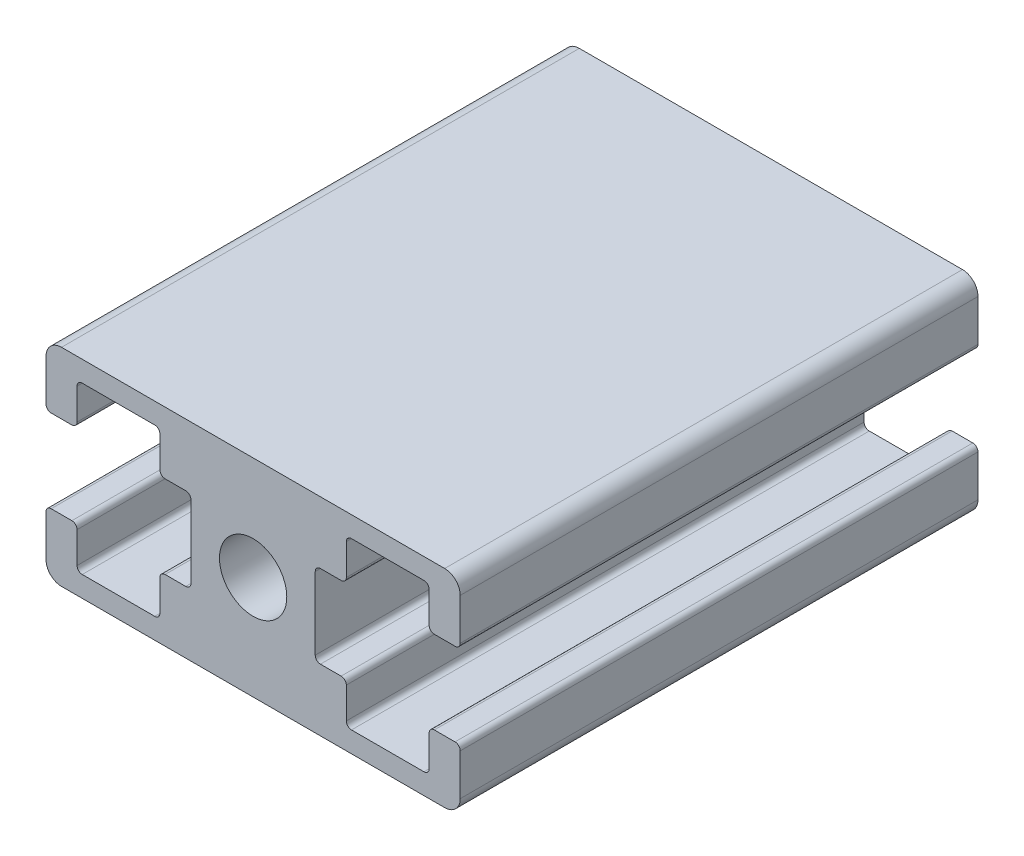
SolidWorks part; units mm, degrees
material "6063-T5"
ref_plane "Front Plane" through (0, 0, 0) normal (0, 0, 1) x (1, 0, 0)
ref_plane "Top Plane" through (0, 0, 0) normal (0, 1, 0) x (1, 0, 0)
ref_plane "Right Plane" through (0, 0, 0) normal (1, 0, 0) x (0, 0, -1)
sketch "Sketch1" plane through (0, 0, 0) normal (0, 0, 1) x (1, 0, 0)
  line L0 (1.5, 0) -> (38.5, 0)
  line L1 (40, 1.5) -> (40, 5.5)
  line L2 (38.5, 20) -> (1.5, 20)
  line L3 (0, 18.5) -> (0, 14.5)
  line L4 (0.5, 14) -> (2.5, 14)
  line L5 (0.5, 6) -> (2.5, 6)
  line L6 (39.5, 14) -> (37.5, 14)
  line L7 (39.5, 6) -> (37.5, 6)
  line L8 (40, 14.5) -> (40, 18.5)
  line L9 (0, 5.5) -> (0, 1.5)
  line L10 (37, 14.5) -> (37, 17.5)
  line L11 (37, 5.5) -> (37, 2.5)
  line L12 (3, 14.5) -> (3, 17.5)
  line L13 (3, 5.5) -> (3, 2.5)
  line L14 (3.5, 18) -> (10.5, 18)
  line L15 (11, 17.5) -> (11, 14.5)
  line L16 (26, 13.5) -> (26, 6.5)
  line L17 (14, 13.5) -> (14, 6.5)
  line L18 (11.5, 14) -> (13.5, 14)
  line L19 (3.5, 2) -> (10.5, 2)
  line L20 (11, 2.5) -> (11, 5.5)
  line L21 (11.5, 6) -> (13.5, 6)
  line L22 (36.5, 18) -> (29.5, 18)
  line L23 (29, 17.5) -> (29, 14.5)
  line L24 (28.5, 14) -> (26.5, 14)
  line L25 (36.5, 2) -> (29.5, 2)
  line L26 (29, 2.5) -> (29, 5.5)
  line L27 (28.5, 6) -> (26.5, 6)
  circle A0 centre (20, 10) radius 3.25
  arc A1 (37, 2.5) -> (36.5, 2) centre (36.5, 2.5) cw
  arc A2 (29.5, 2) -> (29, 2.5) centre (29.5, 2.5) cw
  arc A3 (29, 5.5) -> (28.5, 6) centre (28.5, 5.5) ccw
  arc A4 (26, 6.5) -> (26.5, 6) centre (26.5, 6.5) ccw
  arc A5 (26, 13.5) -> (26.5, 14) centre (26.5, 13.5) cw
  arc A6 (29, 14.5) -> (28.5, 14) centre (28.5, 14.5) cw
  arc A7 (37, 17.5) -> (36.5, 18) centre (36.5, 17.5) ccw
  arc A8 (29.5, 18) -> (29, 17.5) centre (29.5, 17.5) ccw
  arc A9 (10.5, 18) -> (11, 17.5) centre (10.5, 17.5) cw
  arc A10 (11, 14.5) -> (11.5, 14) centre (11.5, 14.5) ccw
  arc A11 (14, 13.5) -> (13.5, 14) centre (13.5, 13.5) ccw
  arc A12 (14, 6.5) -> (13.5, 6) centre (13.5, 6.5) cw
  arc A13 (11, 5.5) -> (11.5, 6) centre (11.5, 5.5) cw
  arc A14 (10.5, 2) -> (11, 2.5) centre (10.5, 2.5) ccw
  arc A15 (3, 2.5) -> (3.5, 2) centre (3.5, 2.5) ccw
  arc A16 (3, 17.5) -> (3.5, 18) centre (3.5, 17.5) cw
  arc A17 (38.5, 0) -> (40, 1.5) centre (38.5, 1.5) ccw
  arc A18 (40, 18.5) -> (38.5, 20) centre (38.5, 18.5) ccw
  arc A19 (1.5, 0) -> (0, 1.5) centre (1.5, 1.5) cw
  arc A20 (1.5, 20) -> (0, 18.5) centre (1.5, 18.5) ccw
  arc A21 (37.5, 6) -> (37, 5.5) centre (37.5, 5.5) ccw
  arc A22 (40, 5.5) -> (39.5, 6) centre (39.5, 5.5) ccw
  arc A23 (37.5, 14) -> (37, 14.5) centre (37.5, 14.5) cw
  arc A24 (40, 14.5) -> (39.5, 14) centre (39.5, 14.5) cw
  arc A25 (0.5, 6) -> (0, 5.5) centre (0.5, 5.5) ccw
  arc A26 (2.5, 6) -> (3, 5.5) centre (2.5, 5.5) cw
  arc A27 (2.5, 14) -> (3, 14.5) centre (2.5, 14.5) ccw
  arc A28 (0.5, 14) -> (0, 14.5) centre (0.5, 14.5) cw
  point P69 (0, 0)
  point P74 (0, 0)
extrude "Boss-Extrude1" add sketch "Sketch1" along normal blind 50
